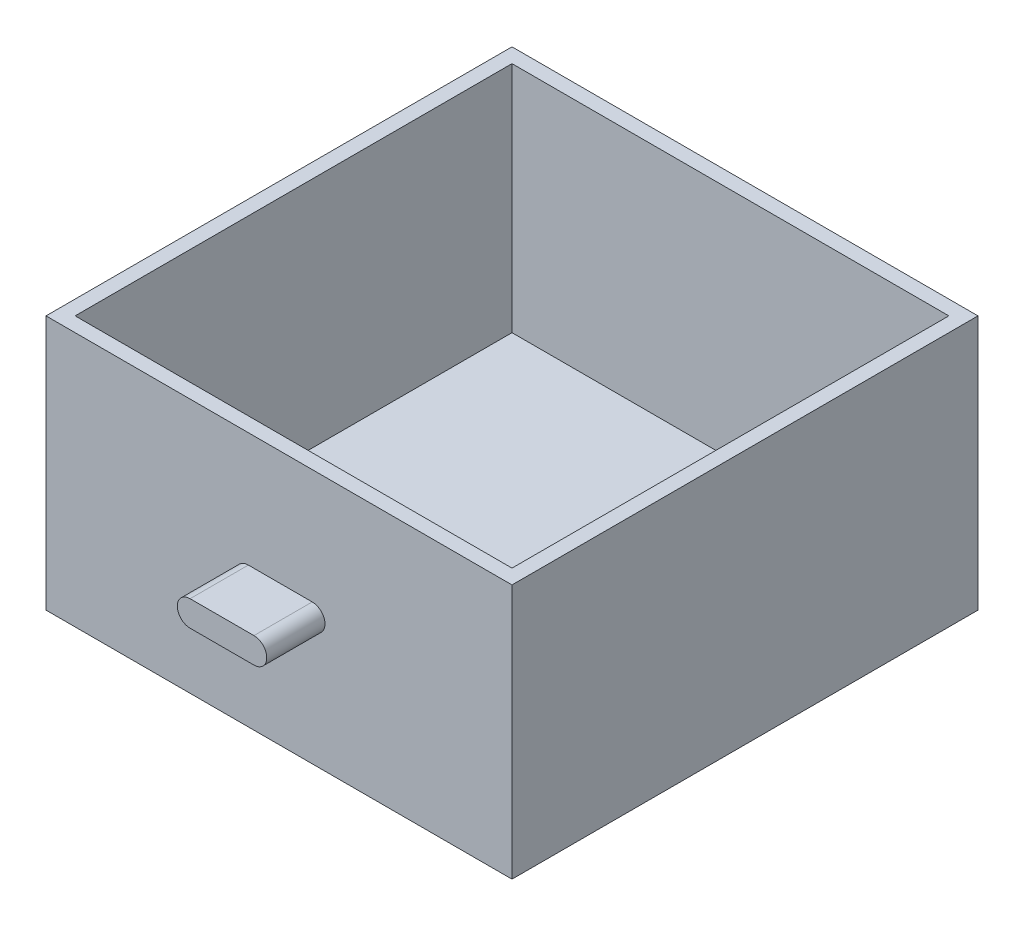
SolidWorks part; units mm, degrees
ref_plane "前视基准面" through (0, 0, 0) normal (0, 0, 1) x (1, 0, 0)
ref_plane "上视基准面" through (0, 0, 0) normal (0, 1, 0) x (1, 0, 0)
ref_plane "右视基准面" through (0, 0, 0) normal (1, 0, 0) x (0, 0, -1)
sketch "草图1" plane through (0, 0, 0) normal (0, 1, 0) x (1, 0, 0)
  line L1 (-30, 30) -> (30, 30)
  line L2 (-30, 30) -> (-30, -30)
  line L3 (-30, -30) -> (30, -30)
  line L4 (30, 30) -> (30, -30)
  line L5 (-30, 30) -> (30, -30) construction
  line L6 (-30, -30) -> (30, 30) construction
  point P0 (0, 0)
  dimension "D1" = 60
  dimension "D2" = 60
extrude "凸台-拉伸1" add sketch "草图1" along normal blind 3
sketch "草图2" plane through (0, 0, 0) normal (0, 1, 0) x (1, 0, 0)
  line L1 (-30, 32) -> (32, 32)
  line L2 (32, 32) -> (32, -32)
  line L3 (32, -32) -> (-32, -32)
  line L4 (-32, -32) -> (-32, 32)
  line L5 (-32, 32) -> (-30, 32)
  line L6 (-30, 30) -> (30, 30)
  line L7 (-30, 30) -> (-30, -30)
  line L8 (-30, -30) -> (30, -30)
  line L9 (30, 30) -> (30, -30)
  line L10 (-30, 30) -> (30, -30) construction
  line L11 (-30, -30) -> (30, 30) construction
  point P0 (0, 0)
extrude "凸台-拉伸2" add sketch "草图2" along normal blind 35
ref_plane "基准面4" through (0, 0, 32) normal (0, 0, 1) x (1, 0, 0)
sketch "草图3" plane through (0, 0, 32) normal (0, 0, 1) x (1, 0, 0)
  line L0 (-4.2107, 17.5) -> (4.562, 17.5) construction
  line L1 (-4.2107, 19.2551) -> (4.562, 19.2551)
  line L2 (-4.2107, 15.7449) -> (4.562, 15.7449)
  arc A0 (-4.2107, 19.2551) -> (-4.2107, 15.7449) centre (-4.2107, 17.5) ccw
  arc A1 (4.562, 15.7449) -> (4.562, 19.2551) centre (4.562, 17.5) ccw
  point P2 (0.1756, 17.5)
extrude "凸台-拉伸3" add sketch "草图3" along normal blind 8
